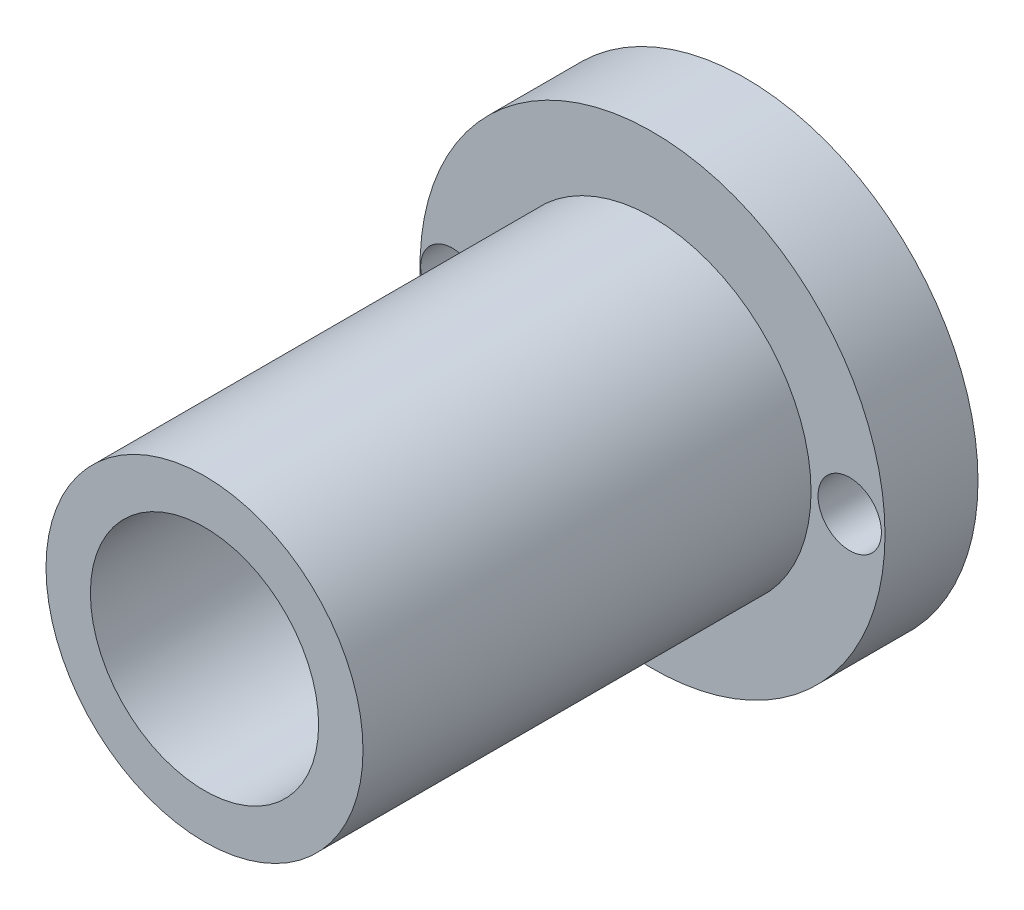
SolidWorks part; units mm, degrees
ref_plane "前视基准面" through (0, 0, 0) normal (0, 0, 1) x (1, 0, 0)
ref_plane "上视基准面" through (0, 0, 0) normal (0, 1, 0) x (1, 0, 0)
ref_plane "右视基准面" through (0, 0, 0) normal (1, 0, 0) x (0, 0, -1)
sketch "草图2" plane through (0, 0, 0) normal (0, 0, 1) x (1, 0, 0)
  circle A0 centre (0, 0) radius 55
  dimension "D1" = 110
extrude "凸台-拉伸2" add sketch "草图2" along normal blind 22
sketch "草图4" plane through (0, 0, 22) normal (0, 0, 1) x (1, 0, 0)
  circle A0 centre (0, 0) radius 27
  circle A1 centre (0, 0) radius 37.5
  dimension "D1" = 54
  dimension "D2" = 75
extrude "凸台-拉伸3" add sketch "草图4" along normal blind 106
sketch "草图5" plane through (0, 0, 22) normal (0, 0, 1) x (1, 0, 0)
  line L0 (0, 0) -> (55, 0)
  line L1 (55, 0) -> (-55, 0) construction
  circle A0 centre (0, 0) radius 55 construction
  circle A1 centre (-47.3564, 0) radius 7.5
  circle A2 centre (46.6498, 0) radius 7.5
  dimension "D1" = 15
  dimension "D2" = 15
extrude "切除-拉伸1" cut sketch "草图5" against normal through all contours L1 A1 | L0 A2 | A1 L1 | L0 A2
sketch "草图6" plane through (0, 0, 22) normal (0, 0, 1) x (1, 0, 0)
  circle A0 centre (0, 0) radius 27
extrude "切除-拉伸2" cut sketch "草图6" against normal through all
